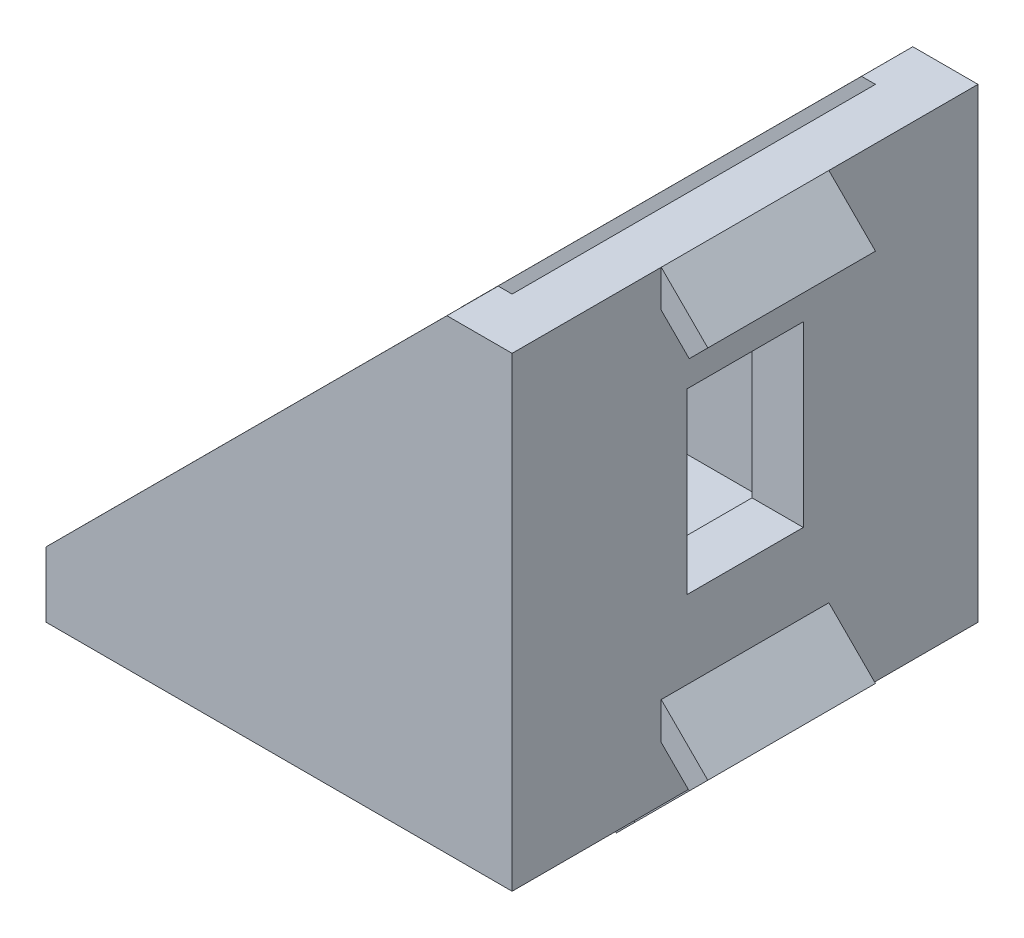
SolidWorks part; units mm, degrees
ref_plane "Front Plane" through (0, 0, 0) normal (0, 0, 1) x (1, 0, 0)
ref_plane "Top Plane" through (0, 0, 0) normal (0, 1, 0) x (1, 0, 0)
ref_plane "Right Plane" through (0, 0, 0) normal (1, 0, 0) x (0, 0, -1)
sketch "Sketch1" plane through (0, 0, 0) normal (0, 0, 1) x (1, 0, 0)
  line L0 (10.2636, 7.7407) -> (10.2636, -10.2593)
  line L1 (10.2636, -10.2593) -> (-7.745, -10.2593)
  line L2 (-7.745, -10.2593) -> (-7.745, -7.7407)
  line L3 (-7.745, -7.7407) -> (7.745, 7.7407)
  line L4 (7.745, 7.7407) -> (10.2636, 7.7407)
  dimension "D1" = 18
  dimension "D2" = 18.0086
  dimension "D3" = 21.9
extrude "Extrude1" add sketch "Sketch1" along normal mid plane 18
sketch "Sketch2" plane through (0, 0, 0) normal (0, 0, 1) x (1, 0, 0)
  line L0 (8.2824, 7.7407) -> (8.2824, -8.2781)
  line L1 (8.2824, -8.2781) -> (-7.745, -8.2781)
  line L2 (-7.745, -8.2781) -> (-7.745, 7.7407)
  line L3 (8.2824, 7.7407) -> (-7.745, 7.7407)
  line L4 (10.2636, 7.7407) -> (7.745, 7.7407) construction
  line L5 (-7.745, -7.7407) -> (-7.745, -10.2593) construction
  line L6 (10.2636, -10.2593) -> (10.2636, 7.7407) construction
  line L7 (-7.745, -10.2593) -> (10.2636, -10.2593) construction
  dimension "D1" = 1.9812
  dimension "D2" = 1.9812
extrude "Cut-Extrude1" cut sketch "Sketch2" along normal offset from surface 1.9812 and the other way offset from surface (7.0188 mm away) 1.9812 up to face at (2.5565, -2.5556, 9) other way up to face at (2.5565, -2.5556, -9)
sketch "Sketch3" plane through (0, -8.2781, 0) normal (0, 1, 0) x (1, 0, 0)
  line L0 (-3.173, 0) -> (3.7104, 0) construction
  line L1 (-3.173, 2.25) -> (3.7104, 2.25)
  line L2 (-3.173, 2.25) -> (-3.173, -2.25)
  line L3 (-3.173, -2.25) -> (3.7104, -2.25)
  line L4 (3.7104, 2.25) -> (3.7104, -2.25)
  line L5 (8.2824, 7.0188) -> (-7.745, 7.0188) construction
  line L7 (-7.745, -7.0188) -> (-7.745, 7.0188) construction
  line L8 (8.2824, -7.0188) -> (8.2824, 7.0188) construction
  line L9 (0.2687, 7.0188) -> (0.2687, 0) construction
  line L10 (-7.745, 7.0188) -> (7.745, 7.0188) construction
  dimension "D1" = 4.5
  dimension "D2" = 6.8834
extrude "Cut-Extrude2" cut sketch "Sketch3" against normal through all
sketch "Sketch4" plane through (8.2824, 0, 0) normal (-1, 0, 0) x (0, 0, 1)
  line L0 (7.0188, -8.2781) -> (7.0188, 7.7407) construction
  line L1 (-2.25, 3.173) -> (2.25, 3.173)
  line L2 (-2.25, 3.173) -> (-2.25, -3.7104)
  line L3 (-2.25, -3.7104) -> (2.25, -3.7104)
  line L4 (2.25, 3.173) -> (2.25, -3.7104)
  line L5 (7.0188, 7.7407) -> (-7.0188, 7.7407) construction
  line L6 (7.0188, -7.7407) -> (7.0188, 7.7407) construction
  line L7 (7.0188, -0.2687) -> (2.25, -0.2687) construction
  line L8 (0, -3.7104) -> (0, 3.173) construction
  line L9 (-2.25, -10.2593) -> (-2.25, -8.2781) construction
  dimension "D1" = 6.8834
extrude "Cut-Extrude3" cut sketch "Sketch4" against normal through all
sketch "Sketch5" plane through (0, 0, 0) normal (0, 0, 1) x (1, 0, 0)
  line L0 (10.2636, 7.7407) -> (12.0636, 5.9397)
  line L1 (12.0636, 5.9397) -> (11.345, 5.2214)
  line L2 (11.345, 5.2214) -> (10.2636, 6.3034)
  line L3 (10.2636, -10.2593) -> (10.2636, 7.7407) construction
  line L4 (10.2636, -8.161) -> (10.2636, -6.7238)
  line L5 (-7.745, -10.2593) -> (-5.946, -12.0593)
  line L6 (-5.946, -12.0593) -> (-5.2273, -11.3411)
  line L7 (-5.2273, -11.3411) -> (-6.3085, -10.2593)
  line L8 (-7.745, -10.2593) -> (10.2636, -10.2593) construction
  line L9 (-7.745, -10.2593) -> (-6.3085, -10.2593)
  line L10 (6.7281, -10.2593) -> (8.5271, -12.0593)
  line L11 (8.5271, -12.0593) -> (9.2457, -11.3411)
  line L12 (9.2457, -11.3411) -> (8.1646, -10.2593)
  line L13 (10.2636, -8.161) -> (11.345, -9.243)
  line L14 (11.345, -9.243) -> (12.0636, -8.5248)
  line L15 (12.0636, -8.5248) -> (10.2636, -6.7238)
  line L16 (7.745, 7.7407) -> (-7.745, -7.7407) construction
  line L17 (6.7281, -10.2593) -> (8.1646, -10.2593)
  line L18 (10.2636, 6.3034) -> (10.2636, 7.7407)
  line L19 (-7.745, -10.2593) -> (10.2636, -10.2593) construction
  line L20 (10.2636, -10.2593) -> (10.2636, 7.7407) construction
  dimension "D1" = 1.8
  dimension "D2" = 1.8
  dimension "D3" = 5
  dimension "D4" = 1.016
extrude "Extrude2" add sketch "Sketch5" along normal mid plane 6.477
equation "\"D1@Sketch4\" = \"D2@Sketch3\""
equation "\"D2@Sketch5\" = \"D1@Sketch5\""
